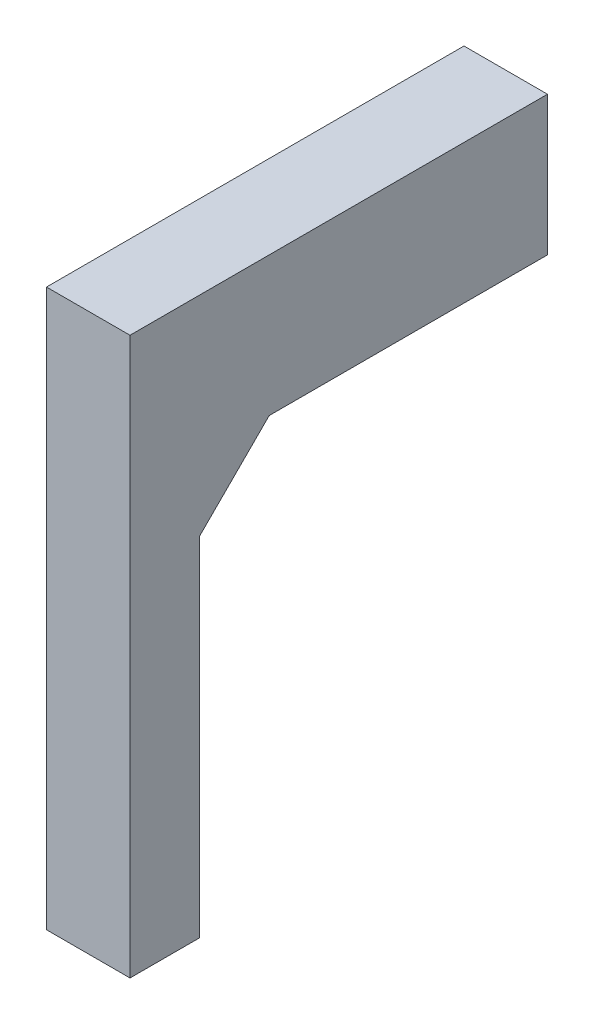
SolidWorks part; units mm, degrees
ref_plane "Front Plane" through (0, 0, 0) normal (1, 0, 0) x (0, 1, 0)
ref_plane "Top Plane" through (0, 0, 0) normal (0, 0, 1) x (0, 1, 0)
ref_plane "Right Plane" through (0, 0, 0) normal (0, 1, 0) x (-1, 0, 0)
sketch "Sketch2" plane through (0, 0, 0) normal (1, 0, 0) x (0, 1, 0)
  line L0 (0, 0) -> (0, 150)
  line L1 (0, 150) -> (-200, 150)
  line L2 (-200, 150) -> (-200, 125)
  line L3 (0, 0) -> (-50, 0)
  line L4 (-50, 0) -> (-50, 100)
  line L5 (-50, 100) -> (-75, 125)
  line L6 (-75, 125) -> (-200, 125)
  dimension "D1" = 150
  dimension "D2" = 200
  dimension "D3" = 25
  dimension "D4" = 50
  dimension "D5" = 100
extrude "Boss-Extrude1" add sketch "Sketch2" along normal blind 30
